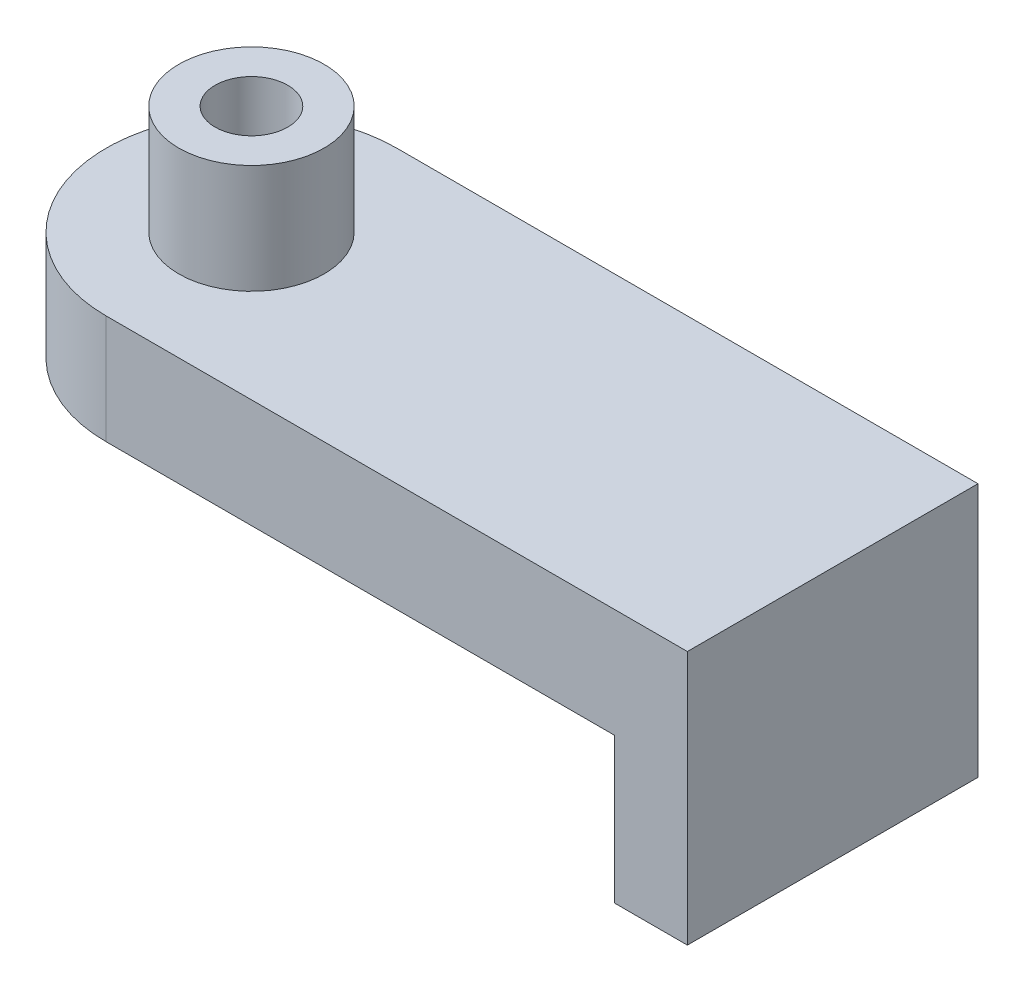
SolidWorks part; units mm, degrees
ref_plane "Alzado" through (0, 0, 0) normal (0, 0, 1) x (1, 0, 0)
ref_plane "Planta" through (0, 0, 0) normal (0, 1, 0) x (1, 0, 0)
ref_plane "Vista lateral" through (0, 0, 0) normal (1, 0, 0) x (0, 0, -1)
sketch "Croquis2" plane through (0, 0, 0) normal (0, 1, 0) x (1, 0, 0)
  line L1 (0, 0) -> (80, 0)
  line L3 (0, 40) -> (80, 40)
  line L4 (80, 0) -> (80, 40)
  arc A0 (0, 40) -> (0, 0) centre (0, 20) ccw
  circle A1 centre (0, 20) radius 5
  dimension "D1" = 80
  dimension "D2" = 40
extrude "Saliente-Extruir1" add sketch "Croquis2" along normal blind 15
sketch "Croquis3" plane through (0, 15, 0) normal (0, 1, 0) x (1, 0, 0)
  circle A0 centre (0, 20) radius 10
  circle A1 centre (0, 20) radius 5
extrude "Saliente-Extruir2" add sketch "Croquis3" along normal blind 15
sketch "Croquis4" plane through (0, 0, 0) normal (0, -1, 0) x (1, 0, 0)
  line L0 (80, -40) -> (0, -40) construction
  line L1 (80, 0) -> (70, 0)
  line L2 (80, 0) -> (80, -40)
  line L3 (80, -40) -> (70, -40)
  line L4 (70, 0) -> (70, -40)
  dimension "D1" = 10
extrude "Saliente-Extruir3" add sketch "Croquis4" along normal blind 20
